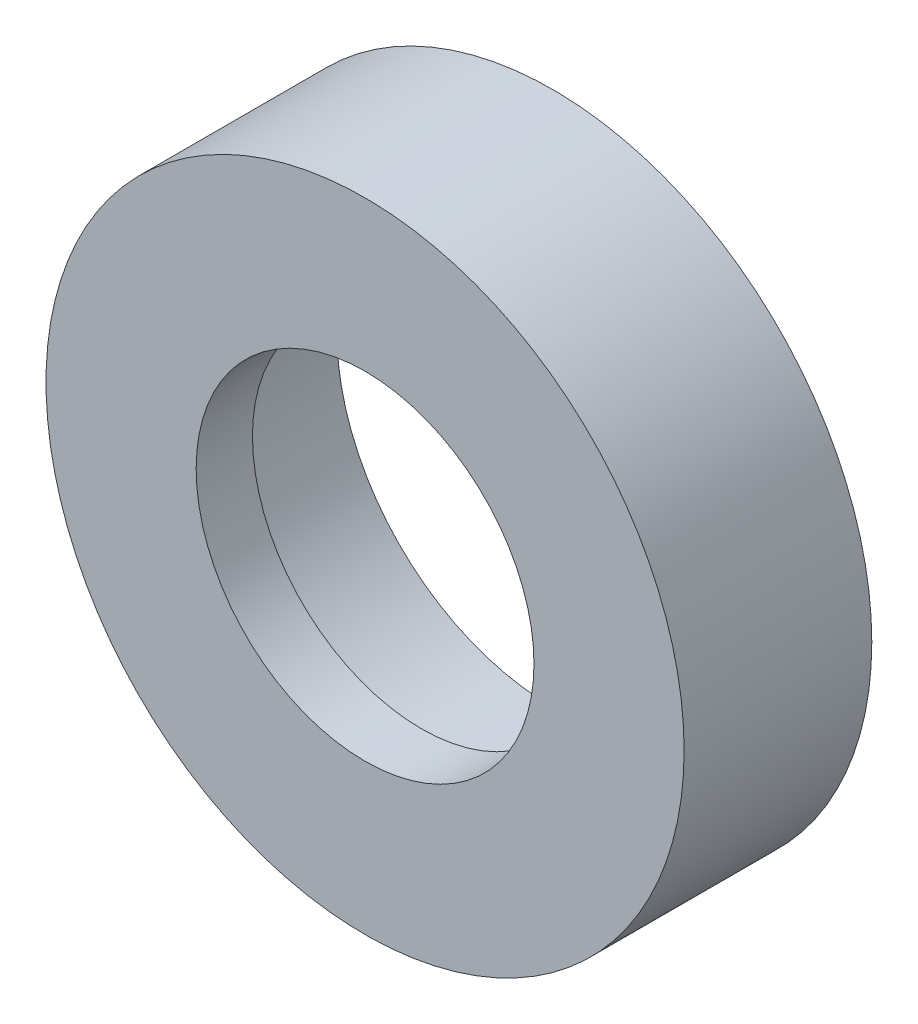
SolidWorks part; units mm, degrees
ref_plane "Спереди" through (0, 0, 0) normal (0, 0, 1) x (1, 0, 0)
ref_plane "Сверху" through (0, 0, 0) normal (0, 1, 0) x (1, 0, 0)
ref_plane "Справа" through (0, 0, 0) normal (1, 0, 0) x (0, 0, -1)
sketch "Эскиз1" plane through (0, 0, 0) normal (0, 0, 1) x (1, 0, 0)
  circle A1 centre (0, 0) radius 11.5
  circle A2 centre (0, 0) radius 17
extrude "Бобышка-Вытянуть1" add sketch "Эскиз1" along normal blind 10
sketch "Эскиз2" plane through (0, 0, 10) normal (0, 0, 1) x (1, 0, 0)
  circle A0 centre (0, 0) radius 9
  circle A1 centre (0, 0) radius 11.5
extrude "Бобышка-Вытянуть2" add sketch "Эскиз2" against normal blind 3
